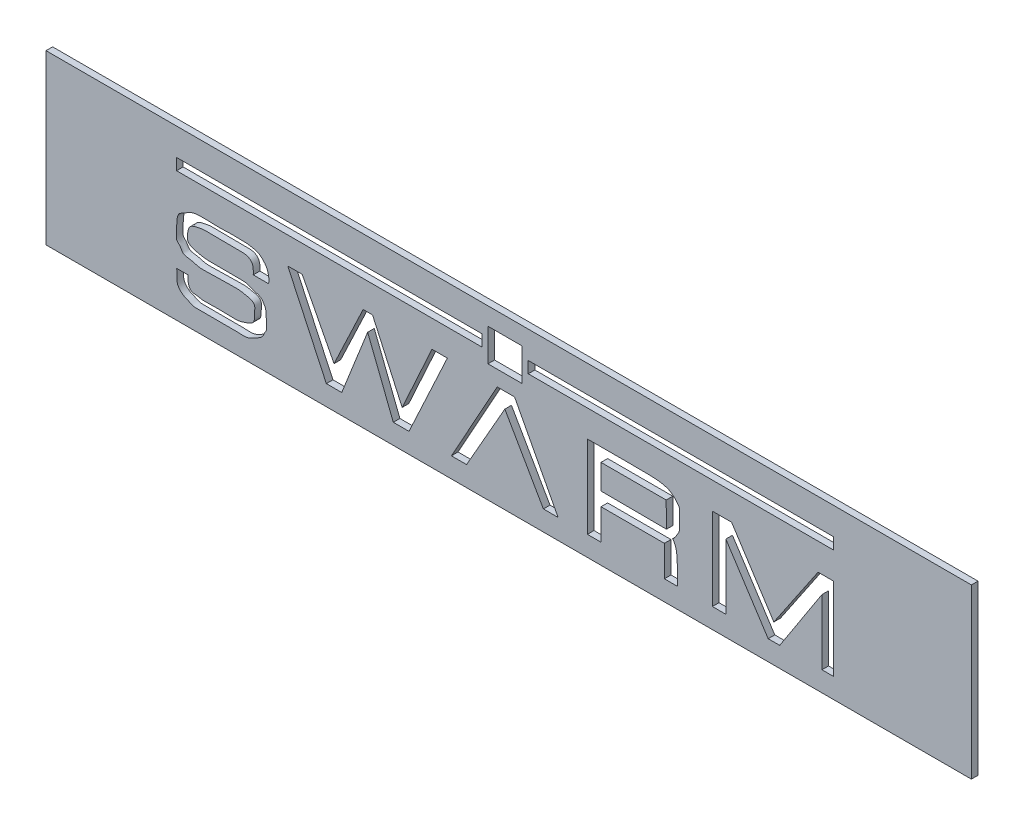
SolidWorks part; units mm, degrees
ref_plane "Front Plane" through (0, 0, 0) normal (0, 0, 1) x (1, 0, 0)
ref_plane "Top Plane" through (0, 0, 0) normal (0, 1, 0) x (1, 0, 0)
ref_plane "Right Plane" through (0, 0, 0) normal (1, 0, 0) x (0, 0, -1)
sketch "Sketch1" plane through (0, 0, 0) normal (0, 0, 1) x (1, 0, 0)
  line L1 (-222.25, -40.4) -> (222.25, -40.4)
  line L2 (-222.25, -40.4) -> (-222.25, 40.4)
  line L3 (-222.25, 40.4) -> (222.25, 40.4)
  line L4 (222.25, -40.4) -> (222.25, 40.4)
  line L5 (-222.25, -40.4) -> (222.25, 40.4) construction
  line L6 (-222.25, 40.4) -> (222.25, -40.4) construction
  point P0 (0, 0)
  dimension "D1" = 80.8
  dimension "D2" = 444.5
sketch "Sketch2" plane through (0, 0, 0) normal (0, 0, 1) x (1, 0, 0)
  line L0 (-115.5, 3.8386) -> (141.8333, 3.8386) construction
  line L1 (148.6027, 8.8845) -> (155.9618, 8.8845)
  line L2 (-222.25, -40.4) -> (222.25, 40.4) construction
  line L3 (-122.7062, -3.1004) -> (-115.2991, -3.1004)
  line L4 (-159.538, -18.7768) -> (-153.9559, -18.7768)
  line L11 (-106.1193, 8.8868) -> (-99.1852, 8.8868)
  line L12 (-99.1852, 8.8868) -> (-83.8919, -20.6337)
  line L13 (-83.8919, -20.6337) -> (-69.9228, 8.8868)
  line L14 (-51.166, -22.4751) -> (-36.8436, 8.8868)
  line L15 (-36.8436, 8.8868) -> (-29.4635, 8.8868)
  line L16 (-29.4635, 8.8868) -> (-47.8873, -30.7813)
  line L17 (-47.8873, -30.7813) -> (-55.4212, -30.7813)
  line L18 (-55.4212, -30.7813) -> (-67.7538, 0.5106)
  line L19 (-67.7538, 0.5106) -> (-80.2018, -30.7813)
  line L20 (-80.2018, -30.7813) -> (-87.5964, -30.7813)
  line L21 (-87.5964, -30.7813) -> (-106.1193, 8.8868)
  line L22 (-5.5054, 8.8868) -> (2.8245, 8.8868)
  line L23 (2.8245, 8.8868) -> (23.7297, -30.7813)
  line L24 (-69.9228, 8.8868) -> (-65.4074, 8.8868)
  line L25 (23.7297, -30.7813) -> (16.6559, -30.7813)
  line L26 (16.6559, -30.7813) -> (-1.8482, 1.5067)
  line L27 (-1.8482, 1.5067) -> (-20.2384, -30.7813)
  line L28 (-20.2384, -30.7813) -> (-27.5191, -30.7813)
  line L29 (-27.5191, -30.7813) -> (-5.5054, 8.8868)
  line L31 (81.1775, -30.7813) -> (74.7806, -30.7813)
  line L32 (74.7806, -30.7813) -> (74.7806, -16.0211)
  line L33 (74.7806, -16.0211) -> (44.3376, -16.0211)
  line L34 (44.3376, -16.0211) -> (44.3376, -30.7813)
  line L35 (44.3376, -30.7813) -> (37.8018, -30.7813)
  line L36 (37.8018, -30.7813) -> (37.8018, 8.8868)
  line L37 (44.3376, 2.4292) -> (75.6394, 2.4292)
  line L38 (75.6394, 2.4292) -> (75.7843, -9.672)
  line L39 (75.7843, -9.672) -> (44.3376, -9.503)
  line L40 (44.3376, -9.503) -> (44.3376, 2.4292)
  line L41 (97.8434, 8.8868) -> (107.0686, 8.8868)
  line L42 (107.0686, 8.8868) -> (127.3507, -22.4751)
  line L43 (155.9618, 8.8845) -> (155.9618, -30.7813)
  line L44 (155.9618, -30.7813) -> (150.4684, -30.7813)
  line L45 (150.4684, -30.7813) -> (150.4684, 0.5106)
  line L46 (150.4684, 0.5106) -> (130.1759, -30.7813)
  line L47 (104.301, 0.5106) -> (124.6363, -30.7813)
  line L48 (104.301, 0.5106) -> (104.301, -30.7813)
  line L49 (104.301, -30.7813) -> (97.8434, -30.7813)
  line L50 (97.8434, -30.7813) -> (97.8434, 8.8868)
  line L51 (-9.9691, 31.9002) -> (6.4727, 31.9002)
  line L52 (6.4727, 31.9002) -> (6.4727, 16.2669)
  line L53 (6.4727, 16.2669) -> (-9.9691, 16.2669)
  line L54 (-9.9691, 16.2669) -> (-9.9691, 31.9002)
  line L55 (-159.538, 27.3371) -> (-12.8583, 27.3371)
  line L56 (-12.8583, 27.3371) -> (-12.8583, 21.802)
  line L57 (-12.8583, 21.802) -> (-159.538, 21.802)
  line L58 (-159.538, 21.802) -> (-159.538, 27.3371)
  line L59 (9.3917, 27.3371) -> (155.9618, 27.3371)
  line L60 (155.9618, 27.3371) -> (155.9618, 21.802)
  line L61 (155.9618, 21.802) -> (9.3917, 21.802)
  line L62 (9.3917, 21.802) -> (9.3917, 27.3371)
  line L63 (124.6363, -30.7813) -> (130.1759, -30.7813)
  line L64 (127.3507, -22.4751) -> (148.6027, 8.8845)
  line L67 (-65.4074, 8.8868) -> (-51.166, -22.4751)
  spline S0 degree 3 poles (-159.538, -18.7768) (-158.9254, -20.7604) (-160.0338, -24.0067) (-158.0752, -26.8721) (-156.7827, -28.0285) (-155.3542, -28.9608) (-153.6112, -29.4504) (-151.687, -30.7531) (-149.0282, -30.5656) (-146.2488, -30.6388) (-143.4961, -30.5846) (-140.3575, -30.6802) (-137.0635, -30.5774) (-133.5732, -30.7552) (-129.7645, -30.523) (-126.0263, -31.1036) (-123.0954, -29.6567) (-121.0482, -28.6069) (-119.5129, -27.5476) (-117.9806, -26.4963) (-117.5945, -24.7711) (-116.2178, -23.2369) (-116.2729, -21.0512) (-116.4273, -18.9158) (-116.5145, -16.7279) (-116.5335, -14.3629) (-117.6265, -12.5487) (-118.7413, -10.752) (-120.8841, -9.8893) (-123.3213, -8.989) (-126.1285, -8.0284) (-129.1797, -7.9818) (-132.6567, -7.9437) (-136.1662, -7.9641) (-139.6914, -7.8481) (-142.7038, -7.977) (-145.7462, -7.8977) (-149.02, -7.3404) (-151.7998, -6.6205) (-154.3739, -5.1513) (-154.4169, -2.1422) (-153.9842, 0.0177) (-153.3229, 1.4929) (-152.1841, 2.6194) (-149.724, 3.2151) (-147.0515, 3.8096) (-144.5149, 3.8293) (-142.0882, 3.798) (-139.4048, 3.6293) (-136.0192, 3.7204) (-132.4223, 4.025) (-129.0004, 3.7944) (-126.0345, 3.6179) (-122.4792, 1.9389) (-122.6279, -1.5087) (-122.7062, -3.1004) knots 0 0 0 0 0.045054 0.057588 0.06928 0.080802 0.092277 0.106354 0.127202 0.144645 0.164213 0.183717 0.209335 0.232061 0.255492 0.288322 0.306622 0.321383 0.335716 0.345441 0.358195 0.37015 0.38632 0.400449 0.414879 0.431506 0.447942 0.457663 0.474286 0.493165 0.512086 0.534672 0.555463 0.583849 0.606894 0.628074 0.645915 0.669488 0.696094 0.705592 0.727557 0.749037 0.752567 0.760627 0.780862 0.803042 0.817274 0.832853 0.853078 0.872585 0.902546 0.927349 0.942853 0.96434 1 1 1 1
  spline S1 degree 3 poles (-153.9559, -18.7768) (-154.2853, -20.0497) (-153.9987, -25.3376) (-149.6795, -25.0443) (-147.1215, -25.938) (-144.2062, -25.5842) (-141.1377, -25.7328) (-137.6762, -25.5563) (-133.5792, -25.7617) (-129.7458, -25.9711) (-126.6037, -24.8852) (-124.4522, -24.2019) (-122.3335, -22.8729) (-121.9937, -20.2176) (-122.0749, -17.8342) (-121.8324, -15.5926) (-123.3502, -13.8155) (-125.9135, -13.4487) (-129.8454, -12.443) (-133.9826, -12.8819) (-138.2569, -12.8117) (-141.6373, -12.8069) (-145.0401, -12.8841) (-148.8398, -13.1942) (-152.3535, -11.6551) (-156.6863, -11.6717) (-157.6101, -8.5799) (-159.708, -7.277) (-159.5074, -4.5714) (-159.6356, -2.0717) (-159.3386, 0.5626) (-159.2492, 2.8233) (-158.4453, 4.6869) (-157.1747, 5.31) (-155.6278, 6.0415) (-153.4818, 7.7805) (-149.8068, 8.7008) (-146.1857, 8.6827) (-142.9258, 8.5048) (-139.4403, 8.4212) (-135.9096, 8.3715) (-132.1356, 8.7115) (-128.7544, 8.5836) (-125.0497, 8.4839) (-121.9732, 7.8854) (-119.5509, 6.9289) (-118.3925, 5.8138) (-115.7205, 3.2206) (-114.8607, -0.3531) (-115.2991, -3.1004) knots 0 0 0 0 0.044 0.060874 0.079385 0.099252 0.119243 0.142092 0.169518 0.203051 0.218676 0.236484 0.249692 0.266333 0.286428 0.300449 0.309198 0.330906 0.350445 0.392283 0.413701 0.437672 0.460875 0.483404 0.513308 0.540183 0.558429 0.571897 0.586029 0.608414 0.624677 0.639266 0.655062 0.662122 0.667468 0.689978 0.717351 0.742329 0.763638 0.783749 0.813269 0.835402 0.860711 0.882041 0.910691 0.924247 0.934075 0.943084 1 1 1 1
  spline S2 degree 3 poles (78.7325, -12.1243) (80.2175, -13.9645) (80.8639, -17.0237) (80.928, -21.2717) (81.2113, -25.3568) (81.1489, -28.6738) (81.1775, -30.7813) knots 0 0 0 0 0.356856 0.478923 0.668595 1 1 1 1
  spline S3 degree 3 poles (37.8018, 8.8868) (46.202, 8.7772) (56.3558, 8.9982) (68.9426, 8.8085) (74.1648, 8.5004) (77.7762, 7.0094) (79.1056, 5.7569) (80.1469, 5.0761) (80.8071, 3.8559) (81.9789, 2.8637) (82.2399, 0.5694) (82.0396, -1.959) (82.1233, -4.9864) (82.1121, -7.6192) (80.4647, -9.9144) (79.7992, -11.4971) (78.7325, -12.1243) knots 0 0 0 0 0.407287 0.490761 0.61039 0.65871 0.674575 0.698789 0.717498 0.740771 0.770154 0.822864 0.865361 0.917919 0.943853 1 1 1 1
extrude "Boss-Extrude4" add sketch "Sketch1" against normal blind 3.175
extrude "Cut-Extrude1" cut sketch "Sketch2" against normal blind 16.51
